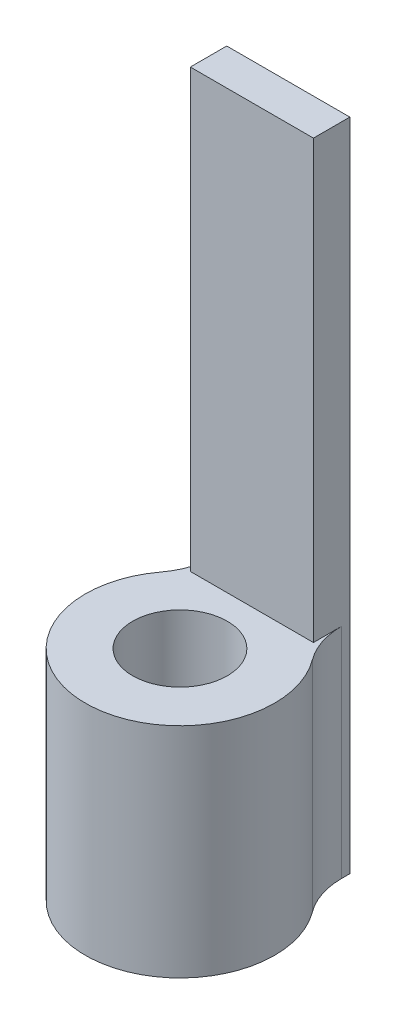
SolidWorks part; units mm, degrees
ref_plane "Front" through (0, 0, 0) normal (0, 0, 1) x (1, 0, 0)
ref_plane "Top" through (0, 0, 0) normal (0, 1, 0) x (1, 0, 0)
ref_plane "Right" through (0, 0, 0) normal (1, 0, 0) x (0, 0, -1)
sketch "Эскиз1" plane through (0, 0, 0) normal (0, 1, 0) x (1, 0, 0)
  line L0 (-1.6908, 1.9752) -> (1.6908, 1.9752)
  circle A0 centre (0, 0) radius 1.3
  arc A1 (-1.6908, 1.9752) -> (1.6908, 1.9752) centre (0, 0) ccw
extrude "Бобышка-Вытянуть1" add sketch "Эскиз1" along normal blind 6
sketch "Эскиз2" plane through (0, 0, 0) normal (0, -1, 0) x (1, 0, 0)
  line L1 (-1.6908, -1.9752) -> (1.6908, -1.9752)
  line L2 (-1.6908, -1.9752) -> (-1.6908, -2.9752)
  line L3 (-1.6908, -2.9752) -> (1.6908, -2.9752)
  line L4 (1.6908, -1.9752) -> (1.6908, -2.9752)
  point P5 (1.6908, -1.9752)
  dimension "D1" = 1
extrude "Бобышка-Вытянуть2" add sketch "Эскиз2" against normal blind 18
fillet "Скругление1" radius 2 2 edges at (1.6908, 3, -1.9752) (-1.6908, 3, -1.9752)
